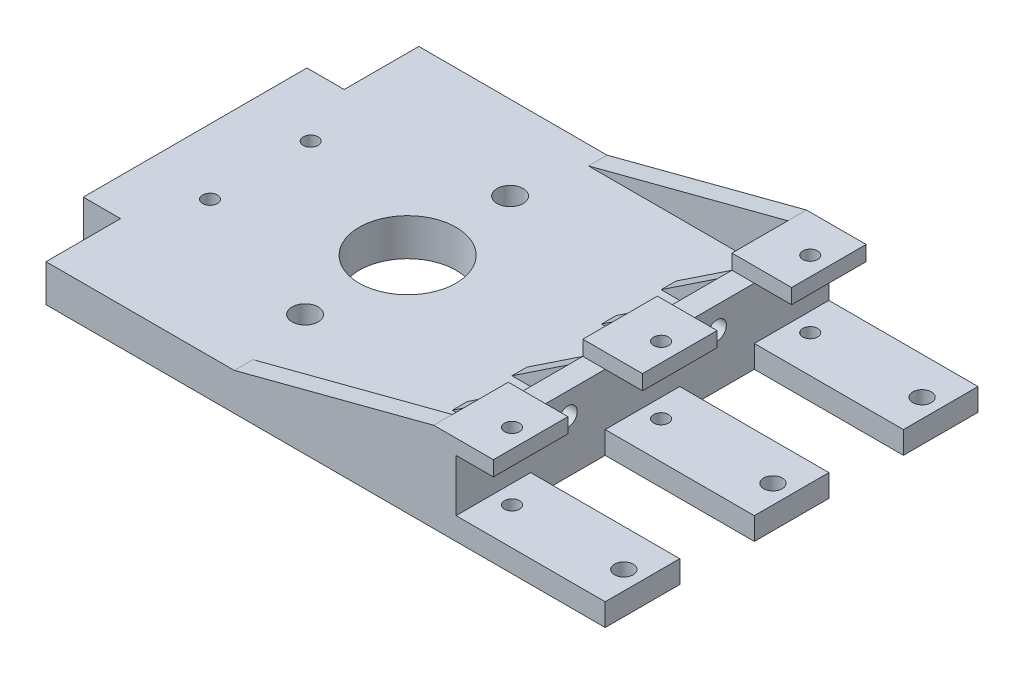
SolidWorks part; units mm, degrees
ref_plane "Front Plane" through (0, 0, 0) normal (0, 0, 1) x (1, 0, 0)
ref_plane "Top Plane" through (0, 0, 0) normal (0, 1, 0) x (1, 0, 0)
ref_plane "Right Plane" through (0, 0, 0) normal (1, 0, 0) x (0, 0, -1)
sketch "Sketch1" plane through (0, 0, 0) normal (0, 1, 0) x (1, 0, 0)
  line L1 (-80, -50) -> (80, -50)
  line L2 (-80, -50) -> (-80, 50)
  line L3 (-80, 50) -> (80, 50)
  line L4 (80, -50) -> (80, 50)
  line L5 (-80, -50) -> (80, 50) construction
  line L6 (-80, 50) -> (80, -50) construction
  point P0 (0, 0)
  dimension "D1" = 100
  dimension "D2" = 160
extrude "Boss-Extrude1" add sketch "Sketch1" along normal blind 10
sketch "Sketch2" plane through (0, 10, 0) normal (0, 1, 0) x (1, 0, 0)
  line L0 (80, 50) -> (80, 30) construction
  line L1 (80, -50) -> (80, 50) construction
  line L2 (80, 10) -> (80, -10) construction
  line L3 (80, 30) -> (40, 30)
  line L4 (80, 30) -> (80, 10)
  line L5 (80, 10) -> (40, 10)
  line L6 (40, 30) -> (40, 10)
  line L8 (80, -10) -> (40, -10)
  line L9 (80, -10) -> (80, -30)
  line L10 (80, -30) -> (40, -30)
  line L11 (40, -10) -> (40, -30)
  dimension "D1" = 20
  dimension "D2" = 20
  dimension "D3" = 40
  dimension "D4" = 20
  dimension "D5" = 20
  dimension "D6" = 40
extrude "Cut-Extrude1" cut sketch "Sketch2" against normal blind 10
sketch "Sketch3" plane through (0, 10, 0) normal (0, 1, 0) x (1, 0, 0)
  line L0 (80, 0) -> (29.4259, 0) construction
  line L1 (40, 30) -> (34, 30)
  line L2 (40, 30) -> (40, 10)
  line L3 (40, 10) -> (34, 10)
  line L4 (34, 30) -> (34, 10)
  line L5 (80, -10) -> (80, 10) construction
  line L6 (40, -10) -> (34, -10)
  line L7 (34, -30) -> (34, -10)
  line L8 (40, -30) -> (34, -30)
  line L9 (40, -30) -> (40, -10)
  dimension "D1" = 20
  dimension "D2" = 6
extrude "Boss-Extrude2" add sketch "Sketch3" along normal blind 10
sketch "Sketch4" plane through (0, 10, 0) normal (0, 1, 0) x (1, 0, 0)
  line L1 (40, 30) -> (80, 30)
  line L2 (40, 30) -> (40, 50)
  line L3 (40, 50) -> (80, 50)
  line L4 (80, 30) -> (80, 50)
  line L5 (40, -10) -> (80, -10)
  line L6 (40, -10) -> (40, 10)
  line L7 (40, 10) -> (80, 10)
  line L8 (80, -10) -> (80, 10)
  line L9 (40, -30) -> (80, -30)
  line L10 (40, -30) -> (40, -50)
  line L11 (40, -50) -> (80, -50)
  line L12 (80, -30) -> (80, -50)
extrude "Cut-Extrude2" cut sketch "Sketch4" against normal blind 4
sketch "Sketch5" plane through (0, 10, 0) normal (0, 1, 0) x (1, 0, 0)
  line L0 (34, 20) -> (17.6264, 20) construction
  line L1 (34, 30) -> (19, 30)
  line L2 (34, 30) -> (34, 26)
  line L3 (34, 26) -> (19, 26)
  line L4 (19, 30) -> (19, 26)
  line L5 (34, 30) -> (34, 10) construction
  line L6 (40, 0) -> (17.6264, 0) construction
  line L7 (40, 10) -> (40, -10) construction
  line L8 (34, 14) -> (19, 14)
  line L9 (19, 10) -> (19, 14)
  line L10 (34, 10) -> (19, 10)
  line L11 (34, 10) -> (34, 14)
  line L12 (34, -10) -> (34, -14)
  line L13 (34, -10) -> (19, -10)
  line L14 (19, -10) -> (19, -14)
  line L15 (34, -14) -> (19, -14)
  line L16 (34, -26) -> (19, -26)
  line L17 (19, -30) -> (19, -26)
  line L18 (34, -30) -> (19, -30)
  line L19 (34, -30) -> (34, -26)
  dimension "D1" = 4
  dimension "D2" = 15
extrude "Boss-Extrude3" add sketch "Sketch5" along normal blind 10
sketch "Sketch6" plane through (0, 0, -30) normal (0, 0, -1) x (-1, 0, 0)
  line L0 (-19, 20) -> (-34, 20) construction
  line L1 (-40, 20) -> (-19, 20) construction
  line L2 (-19, 10) -> (-34, 20)
  line L3 (-34, 20) -> (-19, 20)
  line L4 (-19, 20) -> (-19, 10)
  dimension "D1" = 15
extrude "Cut-Extrude3" cut sketch "Sketch6" against normal blind 100
sketch "Sketch8" plane through (0, 0, 0) normal (0, -1, 0) x (1, 0, 0)
  line L0 (80, 40) -> (75, 40) construction
  line L1 (80, 50) -> (80, 30) construction
  line L2 (80, 0) -> (75, 0) construction
  line L3 (80, 10) -> (80, -10) construction
  line L4 (80, -40) -> (75, -40) construction
  line L5 (80, -30) -> (80, -50) construction
  line L6 (40, -50) -> (40, 50) construction
  line L7 (40, 40) -> (45, 40) construction
  circle A0 centre (75, 40) radius 2.5
  circle A1 centre (75, 0) radius 2.5
  circle A2 centre (75, -40) radius 2.5
  circle A3 centre (45, 40) radius 2
  circle A4 centre (45, 0) radius 2
  circle A5 centre (45, -40) radius 2
  dimension "D2" = 5
  dimension "D4" = 5
  dimension "D5" = 5
  dimension "D7" = 4
  dimension "D8" = 4
  dimension "D9" = 4
  dimension "D1" = 5
  dimension "D3" = 5
  dimension "D6" = 5
extrude "Cut-Extrude4" cut sketch "Sketch8" against normal through all
sketch "Sketch10" plane through (0, 10, 0) normal (0, 1, 0) x (1, 0, 0)
  line L0 (34, 30) -> (40, 30)
  line L1 (40, -50) -> (34, -50)
  line L2 (40, -50) -> (40, -30)
  line L3 (40, 50) -> (34, 50)
  line L4 (34, -50) -> (34, -30)
  line L5 (40, 50) -> (-80, 50) construction
  line L6 (40, 10) -> (34, 10)
  line L7 (40, -10) -> (34, -10)
  line L8 (34, -30) -> (40, -30)
  line L9 (34, -10) -> (34, 10)
  line L10 (40, -10) -> (40, 10)
  line L11 (34, 30) -> (34, 50)
  line L12 (40, 30) -> (40, 50)
  dimension "D1" = 100
extrude "Boss-Extrude5" add sketch "Sketch10" along normal blind 14
sketch "Sketch11" plane through (40, 0, 0) normal (1, 0, 0) x (0, 0, -1)
  line L1 (-30, 20) -> (-50, 20)
  line L2 (-30, 20) -> (-30, 24)
  line L3 (-30, 24) -> (-50, 24)
  line L4 (-50, 20) -> (-50, 24)
  line L5 (10, 20) -> (-10, 20)
  line L6 (10, 20) -> (10, 24)
  line L7 (10, 24) -> (-10, 24)
  line L8 (-10, 20) -> (-10, 24)
  line L9 (30, 20) -> (50, 20)
  line L10 (30, 20) -> (30, 24)
  line L11 (30, 24) -> (50, 24)
  line L12 (50, 20) -> (50, 24)
extrude "Boss-Extrude6" add sketch "Sketch11" along normal blind 10
sketch "Sketch12" plane through (0, 20, 0) normal (0, -1, 0) x (1, 0, 0)
  circle A0 centre (45, 40) radius 2
  circle A1 centre (45, 0) radius 2
  circle A2 centre (45, -40) radius 2
  dimension "D1" = 4
  dimension "D2" = 4
  dimension "D3" = 4
extrude "Cut-Extrude5" cut sketch "Sketch12" against normal blind 10
sketch "Sketch13" plane through (34, 0, 0) normal (-1, 0, 0) x (0, 0, 1)
  line L0 (-20, 20) -> (-20, 14) construction
  line L1 (-26, 20) -> (-14, 20) construction
  line L2 (20, 20) -> (20, 14) construction
  line L3 (14, 20) -> (26, 20) construction
  circle A0 centre (-20, 14) radius 2.5
  circle A1 centre (20, 14) radius 2.5
  dimension "D3" = 5
  dimension "D4" = 5
  dimension "D1" = 6
  dimension "D2" = 6
extrude "Cut-Extrude6" cut sketch "Sketch13" against normal blind 10
sketch "Sketch14" plane through (0, 10, 0) normal (0, 1, 0) x (1, 0, 0)
  line L0 (-80, 50) -> (-80, 30) construction
  line L1 (34, 50) -> (-80, 50) construction
  line L2 (-80, 30) -> (-70, 30)
  line L3 (-80, 30) -> (-80, 50)
  line L4 (-80, 50) -> (-70, 50)
  line L5 (-70, 30) -> (-70, 50)
  line L6 (-80, 50) -> (-80, -50) construction
  line L7 (-80, -50) -> (-70, -50)
  line L8 (-80, -50) -> (-80, -30)
  line L9 (-80, -30) -> (-70, -30)
  line L10 (-70, -50) -> (-70, -30)
  dimension "D1" = 20
  dimension "D2" = 10
  dimension "D3" = 20
  dimension "D4" = 10
extrude "Cut-Extrude7" cut sketch "Sketch14" against normal blind 10
sketch "Sketch15" plane through (0, 10, 0) normal (0, 1, 0) x (1, 0, 0)
  line L0 (34, 0) -> (-23, 0) construction
  line L1 (34, 10) -> (34, -10) construction
  line L2 (-23, 0) -> (-5.3223, 17.6777) construction
  line L3 (-23, 0) -> (-23, 27.5) construction
  line L4 (-23, 27.5) -> (-23, -27.5) construction
  circle A0 centre (-23, 0) radius 13
  circle A10 centre (-23, 27.5) radius 3.5
  circle A11 centre (-23, -27.5) radius 3.5
  point P17 (-23, 0)
  point P20 (-23, 0)
  dimension "D2" = 26
  dimension "D5" = 27.5
  dimension "D7" = 7
  dimension "D8" = 7
  dimension "D1" = 57
  dimension "D3" = 25
  dimension "D4" = 45
  dimension "D6" = 55
sketch "Sketch17" plane through (0, 10, 0) normal (0, 1, 0) x (1, 0, 0)
  line L0 (-70, 30) -> (-70, 13.5) construction
  line L1 (-70, 13.5) -> (-62.5, 13.5) construction
  line L2 (-70, -30) -> (-70, -13.5) construction
  circle A0 centre (-62.5, 13.5) radius 2
  circle A1 centre (-62.5, -13.5) radius 2
  dimension "D3" = 4
  dimension "D5" = 4
  dimension "D1" = 16.5
  dimension "D2" = 7.5
  dimension "D4" = 16.5
extrude "Cut-Extrude8" cut sketch "Sketch17" against normal blind 10
sketch "Sketch18" plane through (-70, 0, 0) normal (-1, 0, 0) x (0, 0, 1)
  line L0 (40, 0) -> (40, 5) construction
  line L1 (50, 0) -> (30, 0) construction
  line L2 (-40, 0) -> (-40, 5) construction
  line L3 (-30, 0) -> (-50, 0) construction
  circle A0 centre (40, 5) radius 2.4
  circle A1 centre (-40, 5) radius 2.4
  dimension "D2" = 4.8
  dimension "D3" = 4.8
  dimension "D1" = 5
extrude "Cut-Extrude9" cut sketch "Sketch18" against normal blind 4
extrude "Cut-Extrude10" cut sketch "Sketch15" against normal blind 10
sketch "Sketch19" plane through (0, 0, -50) normal (0, 0, -1) x (-1, 0, 0)
  line L0 (-34, 24) -> (19.5, 10)
rib "Rib1" sketch "Sketch19" sketch "Sketch19" thickness 5 extrusion direction parallel to sketch draft on no parameters "D1"=5
mirror "Mirror2" about plane through (0, 0, 0) normal (0, 0, 1) of "Rib1"
